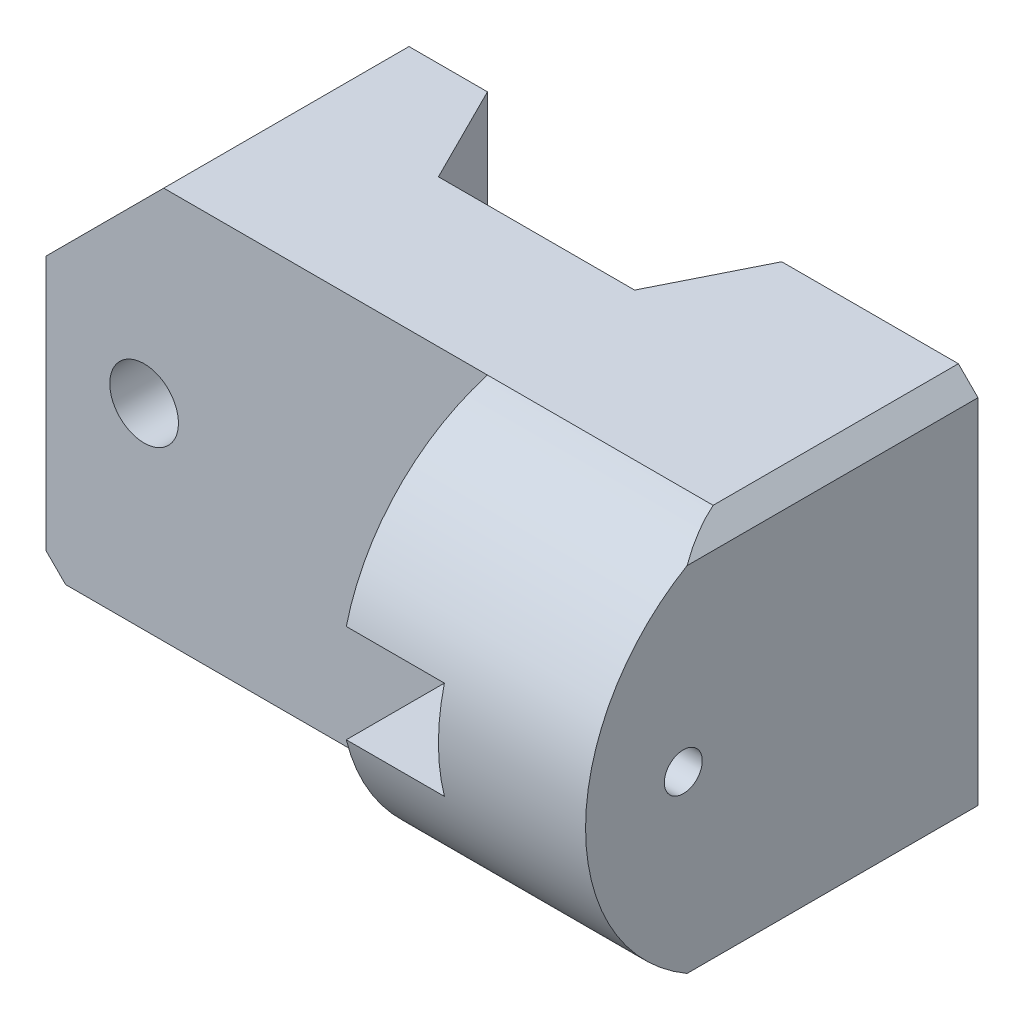
SolidWorks part; units mm, degrees
material "1060 Alloy"
ref_plane "Front Plane" through (0, 0, 0) normal (0, 0, 1) x (1, 0, 0)
ref_plane "Top Plane" through (0, 0, 0) normal (0, 1, 0) x (1, 0, 0)
ref_plane "Right Plane" through (0, 0, 0) normal (1, 0, 0) x (0, 0, -1)
sketch "Sketch1" plane through (0, 0, 0) normal (0, 0, 1) x (1, 0, 0)
  line L0 (-23, 20) -> (-35, 8)
  line L1 (33, 20) -> (-23, 20)
  line L2 (35, 18) -> (35, -18)
  line L3 (33, -20) -> (-33, -20)
  line L4 (-35, 8) -> (-35, -18)
  line L5 (35, 20) -> (-35, -20) construction
  line L6 (35, -20) -> (-35, 20) construction
  line L7 (35, 18) -> (33, 20)
  line L8 (35, -18) -> (33, -20)
  line L9 (-33, -20) -> (-35, -18)
  circle A0 centre (-25, 0) radius 3.5
  point P0 (0, 0)
  dimension "D4" = 7
  dimension "D1" = 40
  dimension "D2" = 70
  dimension "D3" = 25
  dimension "D5" = 20
extrude "Boss-Extrude1" add sketch "Sketch1" along normal mid plane 25
sketch "Sketch2" plane through (0, -20, 0) normal (0, -1, 0) x (1, 0, 0)
  line L0 (0, 0) -> (0, -18.0071) construction
  line L1 (-10, -2.5) -> (10, -2.5)
  line L2 (10, -2.5) -> (15, -12.5)
  line L3 (-33, -12.5) -> (33, -12.5) construction
  line L4 (-10, -2.5) -> (-15, -12.5)
  line L5 (15, -12.5) -> (-15, -12.5)
  point P9 (0, -2.5)
  dimension "D1" = 10
  dimension "D2" = 10
  dimension "D3" = 5
extrude "Cut-Extrude1" cut sketch "Sketch2" against normal through all
sketch "Sketch5" plane through (35, 0, 0) normal (1, 0, 0) x (0, 0, -1)
  line L0 (-12.5, 20) -> (-12.5, -20)
  arc A0 (-12.5, 20) -> (-12.5, -20) centre (-6.6667, 0) ccw
  point P4 (-12.5, 0)
  point P6 (-27.5, 0)
  dimension "D1" = 15
extrude "Boss-Extrude3" add sketch "Sketch5" against normal blind 25
sketch "Sketch6" plane through (0, 0, -12.5) normal (0, 0, -1) x (-1, 0, 0)
  line L0 (-35, 20) -> (-35, 18)
  line L1 (-35, 18) -> (-33, 20)
  line L2 (-35, 18) -> (-33, 20) construction
  line L3 (-33, 20) -> (-35, 20) construction
  line L4 (-33, 20) -> (-35, 20)
  line L5 (-35, -20) -> (-33, -20)
  line L6 (-33, -20) -> (-35, -18)
  line L7 (-35, -18) -> (-35, -20)
extrude "Cut-Extrude2" cut sketch "Sketch6" against normal through all
sketch "Sketch8" plane through (0, 0, 12.5) normal (0, 0, 1) x (1, 0, 0)
  line L1 (10, 5) -> (20, 5)
  line L2 (10, 5) -> (10, -5)
  line L3 (10, -5) -> (20, -5)
  line L4 (20, 5) -> (20, -5)
  line L5 (10, 5) -> (20, -5) construction
  line L6 (10, -5) -> (20, 5) construction
  point P0 (15, 0)
  point P7 (0, 0)
  point P9 (10, 0)
  point P10 (30, 0)
  dimension "D1" = 10
  dimension "D2" = 10
  dimension "D3" = 15
extrude "Cut-Extrude3" cut sketch "Sketch8" along normal through all
sketch "Sketch9" plane through (20, 0, 0) normal (-1, 0, 0) x (0, 0, 1)
  circle A0 centre (17.54, 0) radius 1.9348
extrude "Cut-Extrude4" cut sketch "Sketch9" against normal through all
